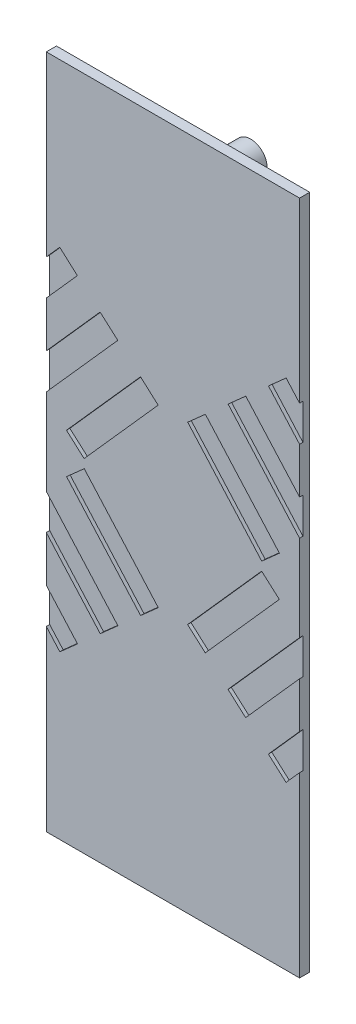
SolidWorks part; units mm, degrees
ref_plane "Front Plane" through (0, 0, 0) normal (0, 0, 1) x (1, 0, 0)
ref_plane "Top Plane" through (0, 0, 0) normal (0, 1, 0) x (1, 0, 0)
ref_plane "Right Plane" through (0, 0, 0) normal (1, 0, 0) x (0, 0, -1)
sketch "Sketch1" plane through (0, 0, 0) normal (0, 0, 1) x (1, 0, 0)
  line L1 (0, 0) -> (225, 0)
  line L2 (0, 0) -> (0, 200)
  line L3 (0, 200) -> (225, 200)
  line L4 (225, 0) -> (225, 200)
  dimension "D1" = 225
  dimension "D2" = 200
extrude "Boss-Extrude1" add sketch "Sketch1" along normal blind 3
sketch "Sketch2" plane through (0, 0, 3) normal (0, 0, 1) x (1, 0, 0)
  line L0 (0, 200) -> (225, 0) construction
  line L1 (225, 200) -> (0, 0) construction
  line L2 (21.1766, 159.1001) -> (43.1006, 183.7646)
  line L3 (9.218, 169.7299) -> (31.1421, 194.3944)
  line L4 (9.218, 169.7299) -> (14.4499, 165.0794)
  line L5 (14.4499, 165.0794) -> (36.3739, 189.7439)
  line L6 (31.1421, 194.3944) -> (36.3739, 189.7439)
  line L7 (21.1766, 159.1001) -> (26.4085, 154.4496)
  line L8 (26.4085, 154.4496) -> (48.3325, 179.1141)
  line L9 (43.1006, 183.7646) -> (48.3325, 179.1141)
  line L10 (33.1351, 148.4703) -> (55.0592, 173.1348)
  line L11 (33.1351, 148.4703) -> (38.367, 143.8197)
  line L12 (38.367, 143.8197) -> (60.291, 168.4842)
  line L13 (55.0592, 173.1348) -> (60.291, 168.4842)
  line L14 (45.0937, 137.8405) -> (67.0177, 162.505)
  line L15 (45.0937, 137.8405) -> (50.3256, 133.1899)
  line L16 (50.3256, 133.1899) -> (72.2496, 157.8544)
  line L17 (67.0177, 162.505) -> (72.2496, 157.8544)
  line L18 (57.0522, 127.2106) -> (78.9763, 151.8751)
  line L19 (57.0522, 127.2106) -> (62.2841, 122.5601)
  line L20 (62.2841, 122.5601) -> (84.2081, 147.2246)
  line L21 (78.9763, 151.8751) -> (84.2081, 147.2246)
  line L22 (69.0108, 116.5808) -> (90.9348, 141.2453)
  line L23 (69.0108, 116.5808) -> (74.2427, 111.9303)
  line L24 (74.2427, 111.9303) -> (96.1667, 136.5948)
  line L25 (90.9348, 141.2453) -> (96.1667, 136.5948)
  line L26 (80.9693, 105.951) -> (102.8933, 130.6155)
  line L27 (80.9693, 105.951) -> (86.2012, 101.3004)
  line L28 (86.2012, 101.3004) -> (108.1252, 125.965)
  line L29 (102.8933, 130.6155) -> (108.1252, 125.965)
  line L38 (116.845, 74.0615) -> (138.769, 98.726)
  line L39 (116.845, 74.0615) -> (122.0769, 69.411)
  line L40 (122.0769, 69.411) -> (144.0009, 94.0755)
  line L41 (138.769, 98.726) -> (144.0009, 94.0755)
  line L42 (128.8035, 63.4317) -> (150.7275, 88.0962)
  line L43 (128.8035, 63.4317) -> (134.0354, 58.7812)
  line L44 (134.0354, 58.7812) -> (155.9594, 83.4457)
  line L45 (150.7275, 88.0962) -> (155.9594, 83.4457)
  line L46 (140.7621, 52.8019) -> (162.6861, 77.4664)
  line L47 (140.7621, 52.8019) -> (145.994, 48.1513)
  line L48 (145.994, 48.1513) -> (167.918, 72.8158)
  line L49 (162.6861, 77.4664) -> (167.918, 72.8158)
  line L50 (152.7206, 42.1721) -> (174.6446, 66.8366)
  line L51 (152.7206, 42.1721) -> (157.9525, 37.5215)
  line L52 (157.9525, 37.5215) -> (179.8765, 62.186)
  line L53 (174.6446, 66.8366) -> (179.8765, 62.186)
  line L54 (164.6792, 31.5422) -> (186.6032, 56.2068)
  line L55 (164.6792, 31.5422) -> (169.9111, 26.8917)
  line L56 (169.9111, 26.8917) -> (191.8351, 51.5562)
  line L57 (186.6032, 56.2068) -> (191.8351, 51.5562)
  line L58 (176.6377, 20.9124) -> (198.5617, 45.5769)
  line L59 (176.6377, 20.9124) -> (181.8696, 16.2619)
  line L60 (181.8696, 16.2619) -> (203.7936, 40.9264)
  line L61 (198.5617, 45.5769) -> (203.7936, 40.9264)
  line L62 (188.5963, 10.2826) -> (210.5203, 34.9471)
  line L63 (188.5963, 10.2826) -> (193.8281, 5.6321)
  line L64 (193.8281, 5.6321) -> (215.7522, 30.2966)
  line L65 (210.5203, 34.9471) -> (215.7522, 30.2966)
  line L66 (198.5915, 154.4496) -> (176.6675, 179.1141)
  line L67 (210.5501, 165.0794) -> (188.6261, 189.7439)
  line L68 (210.5501, 165.0794) -> (215.782, 169.7299)
  line L69 (215.782, 169.7299) -> (193.8579, 194.3944)
  line L70 (188.6261, 189.7439) -> (193.8579, 194.3944)
  line L71 (198.5915, 154.4496) -> (203.8234, 159.1001)
  line L72 (203.8234, 159.1001) -> (181.8994, 183.7646)
  line L73 (176.6675, 179.1141) -> (181.8994, 183.7646)
  line L74 (186.633, 143.8197) -> (164.709, 168.4842)
  line L75 (186.633, 143.8197) -> (191.8649, 148.4703)
  line L76 (191.8649, 148.4703) -> (169.9408, 173.1348)
  line L77 (164.709, 168.4842) -> (169.9408, 173.1348)
  line L78 (174.6744, 133.1899) -> (152.7504, 157.8544)
  line L79 (174.6744, 133.1899) -> (179.9063, 137.8405)
  line L80 (179.9063, 137.8405) -> (157.9823, 162.505)
  line L81 (152.7504, 157.8544) -> (157.9823, 162.505)
  line L82 (162.7159, 122.5601) -> (140.7919, 147.2246)
  line L83 (162.7159, 122.5601) -> (167.9478, 127.2106)
  line L84 (167.9478, 127.2106) -> (146.0237, 151.8751)
  line L85 (140.7919, 147.2246) -> (146.0237, 151.8751)
  line L86 (150.7573, 111.9303) -> (128.8333, 136.5948)
  line L87 (150.7573, 111.9303) -> (155.9892, 116.5808)
  line L88 (155.9892, 116.5808) -> (134.0652, 141.2453)
  line L89 (128.8333, 136.5948) -> (134.0652, 141.2453)
  line L90 (138.7988, 101.3004) -> (116.8748, 125.965)
  line L91 (138.7988, 101.3004) -> (144.0307, 105.951)
  line L92 (144.0307, 105.951) -> (122.1067, 130.6155)
  line L93 (116.8748, 125.965) -> (122.1067, 130.6155)
  line L102 (102.9231, 69.411) -> (80.9991, 94.0755)
  line L103 (102.9231, 69.411) -> (108.155, 74.0615)
  line L104 (108.155, 74.0615) -> (86.231, 98.726)
  line L105 (80.9991, 94.0755) -> (86.231, 98.726)
  line L106 (90.9646, 58.7812) -> (69.0406, 83.4457)
  line L107 (90.9646, 58.7812) -> (96.1965, 63.4317)
  line L108 (96.1965, 63.4317) -> (74.2725, 88.0962)
  line L109 (69.0406, 83.4457) -> (74.2725, 88.0962)
  line L110 (79.006, 48.1513) -> (57.082, 72.8158)
  line L111 (79.006, 48.1513) -> (84.2379, 52.8019)
  line L112 (84.2379, 52.8019) -> (62.3139, 77.4664)
  line L113 (57.082, 72.8158) -> (62.3139, 77.4664)
  line L114 (67.0475, 37.5215) -> (45.1235, 62.186)
  line L115 (67.0475, 37.5215) -> (72.2794, 42.1721)
  line L116 (72.2794, 42.1721) -> (50.3554, 66.8366)
  line L117 (45.1235, 62.186) -> (50.3554, 66.8366)
  line L118 (55.0889, 26.8917) -> (33.1649, 51.5562)
  line L119 (55.0889, 26.8917) -> (60.3208, 31.5422)
  line L120 (60.3208, 31.5422) -> (38.3968, 56.2068)
  line L121 (33.1649, 51.5562) -> (38.3968, 56.2068)
  line L122 (43.1304, 16.2619) -> (21.2064, 40.9264)
  line L123 (43.1304, 16.2619) -> (48.3623, 20.9124)
  line L124 (48.3623, 20.9124) -> (26.4383, 45.5769)
  line L125 (21.2064, 40.9264) -> (26.4383, 45.5769)
  line L126 (31.1719, 5.6321) -> (9.2478, 30.2966)
  line L127 (31.1719, 5.6321) -> (36.4037, 10.2826)
  line L128 (36.4037, 10.2826) -> (14.4797, 34.9471)
  line L129 (9.2478, 30.2966) -> (14.4797, 34.9471)
  line L130 (92.9279, 95.3212) -> (114.8519, 119.9857) [skipped]
  line L131 (98.1598, 90.6706) -> (120.0838, 115.3351) [skipped]
  line L132 (114.8519, 119.9857) -> (120.0838, 115.3351) [skipped]
  line L133 (126.8402, 90.6706) -> (104.9162, 115.3351) [skipped]
  line L134 (132.0721, 95.3212) -> (110.1481, 119.9857) [skipped]
  line L135 (104.9162, 115.3351) -> (110.1481, 119.9857) [skipped]
  line L136 (104.8864, 84.6914) -> (126.8104, 109.3559) [skipped]
  line L137 (104.8864, 84.6914) -> (110.1183, 80.0408) [skipped]
  line L138 (110.1183, 80.0408) -> (132.0423, 104.7053) [skipped]
  line L139 (114.8817, 80.0408) -> (92.9577, 104.7053) [skipped]
  line L140 (114.8817, 80.0408) -> (120.1136, 84.6914) [skipped]
  line L141 (120.1136, 84.6914) -> (98.1896, 109.3559) [skipped]
  line L142 (126.8402, 90.6706) -> (132.0721, 95.3212) [skipped]
  line L143 (126.8104, 109.3559) -> (132.0423, 104.7053) [skipped]
  line L144 (92.9577, 104.7053) -> (98.1896, 109.3559) [skipped]
  line L145 (92.9279, 95.3212) -> (98.1598, 90.6706) [skipped]
  point P12 (20.1801, 182.0622)
  point P79 (199.5881, 177.4116)
  dimension "D1" = 33
  dimension "D2" = 7
  dimension "D3" = 33
  dimension "D5" = 27
  dimension "D6" = 33
  dimension "D7" = 7
  dimension "D8" = 33
  dimension "D9" = 27
  dimension "D4" = 16
  dimension "D10" = 16
extrude "Cut-Extrude1" cut sketch "Sketch2" against normal blind 1
sketch "Sketch4" plane through (0, 0, 0) normal (0, 0, -1) x (-1, 0, 0)
  line L0 (0, 200) -> (0, 0) construction
  line L1 (-212.5, 200) -> (-12.5, 200)
  line L2 (-212.5, 200) -> (-212.5, 0)
  line L3 (-212.5, 0) -> (-12.5, 0)
  line L4 (-12.5, 200) -> (-12.5, 0)
  line L5 (0, 0) -> (-225, 0) construction
  line L7 (0, 200) -> (-75, 200)
  line L8 (0, 200) -> (0, 0)
  line L9 (-225, 200) -> (-150, 200)
  line L10 (-225, 200) -> (-225, 0)
  line L11 (-225, 0) -> (-150, 0)
  line L12 (-150, 200) -> (-150, 0)
  line L13 (0, 0) -> (-75, 0)
  line L14 (-75, 200) -> (-75, 0)
  circle A0 centre (-202.5, 190) radius 4.9
  circle A1 centre (-160, 10) radius 4.9
  circle A2 centre (-122.5, 190) radius 4.9
  circle A3 centre (-102.5, 10) radius 4.9
  circle A4 centre (-42.5, 190) radius 4.9
  circle A5 centre (-22.5, 10) radius 4.9
  point P29 (0, 0)
  dimension "D4" = 10
  dimension "D5" = 9.8
  dimension "D6" = 10
  dimension "D7" = 10
  dimension "D8" = 10
  dimension "D9" = 12.5
  dimension "D1" = 9.8
  dimension "D11" = 80
  dimension "D12" = 20
  dimension "D13" = 20
  dimension "D14" = 80
  dimension "D15" = 9.8
  dimension "D16" = 9.8
  dimension "D17" = 9.8
  dimension "D18" = 9.8
  dimension "D2" = 12.5
  dimension "D3" = 75
  dimension "D10" = 75
extrude "Boss-Extrude2" add sketch "Sketch4" along normal blind 10 contours A3 | A2
sketch "Sketch5" plane through (0, 0, 0) normal (0, 0, -1) x (-1, 0, 0)
  line L0 (0, 0) -> (-225, 0) construction
  line L1 (0, 200) -> (-75, 200)
  line L2 (0, 200) -> (0, 0)
  line L3 (0, 0) -> (-75, 0)
  line L4 (-75, 200) -> (-75, 0)
  line L6 (-225, 200) -> (-150, 200)
  line L7 (-225, 200) -> (-225, 0)
  line L8 (-225, 0) -> (-150, 0)
  line L9 (-150, 200) -> (-150, 0)
  dimension "D1" = 75
  dimension "D2" = 75
extrude "Cut-Extrude2" cut sketch "Sketch5" against normal blind 10
